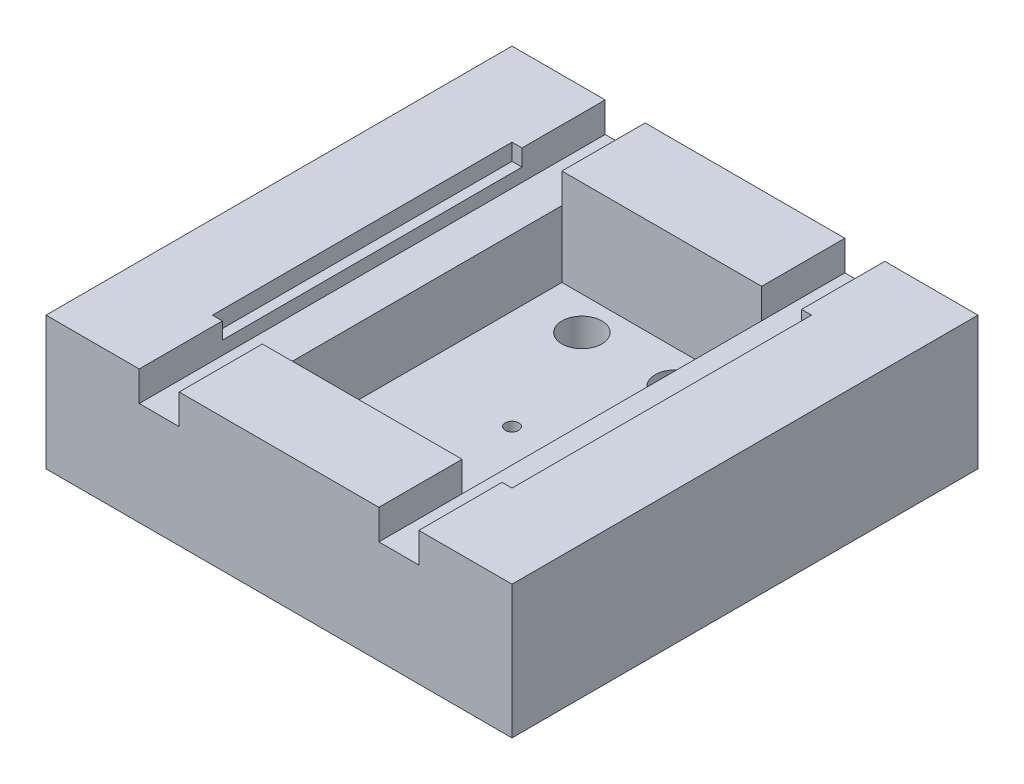
SolidWorks part; units mm, degrees
ref_plane "Alzado" through (0, 0, 0) normal (0, 0, 1) x (1, 0, 0)
ref_plane "Planta" through (0, 0, 0) normal (0, 1, 0) x (1, 0, 0)
ref_plane "Vista lateral" through (0, 0, 0) normal (1, 0, 0) x (0, 0, -1)
sketch "Croquis1" plane through (0, 0, 0) normal (0, 1, 0) x (1, 0, 0)
  line L1 (0, 0) -> (70, 0)
  line L2 (0, 0) -> (0, 70)
  line L3 (0, 70) -> (70, 70)
  line L4 (70, 0) -> (70, 70)
  dimension "D1" = 70
extrude "Saliente-Extruir1" add sketch "Croquis1" along normal blind 20
sketch "Croquis2" plane through (0, 20, 0) normal (0, 1, 0) x (1, 0, 0)
  line L8 (12.5, 57.5) -> (12.5, 12.5)
  line L9 (12.5, 12.5) -> (57.5, 12.5)
  line L10 (57.5, 12.5) -> (57.5, 57.5)
  line L11 (57.5, 57.5) -> (12.5, 57.5)
  line L12 (12.5, 57.5) -> (12.5, 12.5)
  line L13 (12.5, 12.5) -> (57.5, 12.5)
  line L14 (57.5, 12.5) -> (57.5, 57.5)
  line L15 (57.5, 57.5) -> (12.5, 57.5)
  dimension "D1" = 12.5
extrude "Cortar-Extruir1" cut sketch "Croquis2" against normal blind 2.5
sketch "Croquis3" plane through (0, 17.5, 0) normal (0, 1, 0) x (1, 0, 0)
  line L0 (0, 0) -> (70, 0) construction
  line L1 (50, 0) -> (56, 0)
  line L2 (50, 0) -> (50, 70)
  line L3 (50, 70) -> (56, 70)
  line L4 (56, 0) -> (56, 70)
  line L5 (70, 70) -> (0, 70) construction
  line L6 (35, 0) -> (35, 70) construction
  line L7 (57.5, 12.5) -> (57.5, 57.5) construction
  line L8 (20, 0) -> (14, 0)
  line L9 (14, 0) -> (14, 70)
  line L10 (20, 0) -> (20, 70)
  line L11 (20, 70) -> (14, 70)
  dimension "D1" = 6
  dimension "D2" = 1.5
extrude "Cortar-Extruir2" cut sketch "Croquis3" against normal blind 2 and the other way blind 12.5
sketch "Croquis4" plane through (0, 17.5, 0) normal (0, 1, 0) x (1, 0, 0)
  line L4 (20, 12.5) -> (50, 12.5)
  line L5 (50, 12.5) -> (50, 57.5)
  line L6 (50, 57.5) -> (20, 57.5)
  line L7 (20, 57.5) -> (20, 12.5)
  line L8 (20, 12.5) -> (50, 12.5)
  line L9 (50, 12.5) -> (50, 57.5)
  line L10 (50, 57.5) -> (20, 57.5)
  line L11 (20, 57.5) -> (20, 12.5)
  dimension "D1" = 0
extrude "Cortar-Extruir3" cut sketch "Croquis4" against normal blind 12
sketch "Croquis5" plane through (0, 5.5, 0) normal (0, 1, 0) x (1, 0, 0)
  line L0 (20, 35) -> (50, 35) construction
  line L1 (20, 57.5) -> (20, 12.5) construction
  line L2 (50, 12.5) -> (50, 57.5) construction
  line L3 (35, 35) -> (35, 17.5) construction
  line L4 (28, 17.5) -> (42, 17.5) construction
  circle A0 centre (28, 17.5) radius 3
  circle A1 centre (42, 17.5) radius 3
  circle A2 centre (42, 52.5) radius 3
  circle A3 centre (28, 52.5) radius 3
  circle A4 centre (35, 35) radius 1
  point P10 (35, 17.5)
  dimension "D3" = 6
  dimension "D4" = 2
  dimension "D1" = 14
  dimension "D2" = 17.5
extrude "Cortar-Extruir4" cut sketch "Croquis5" against normal blind 11
